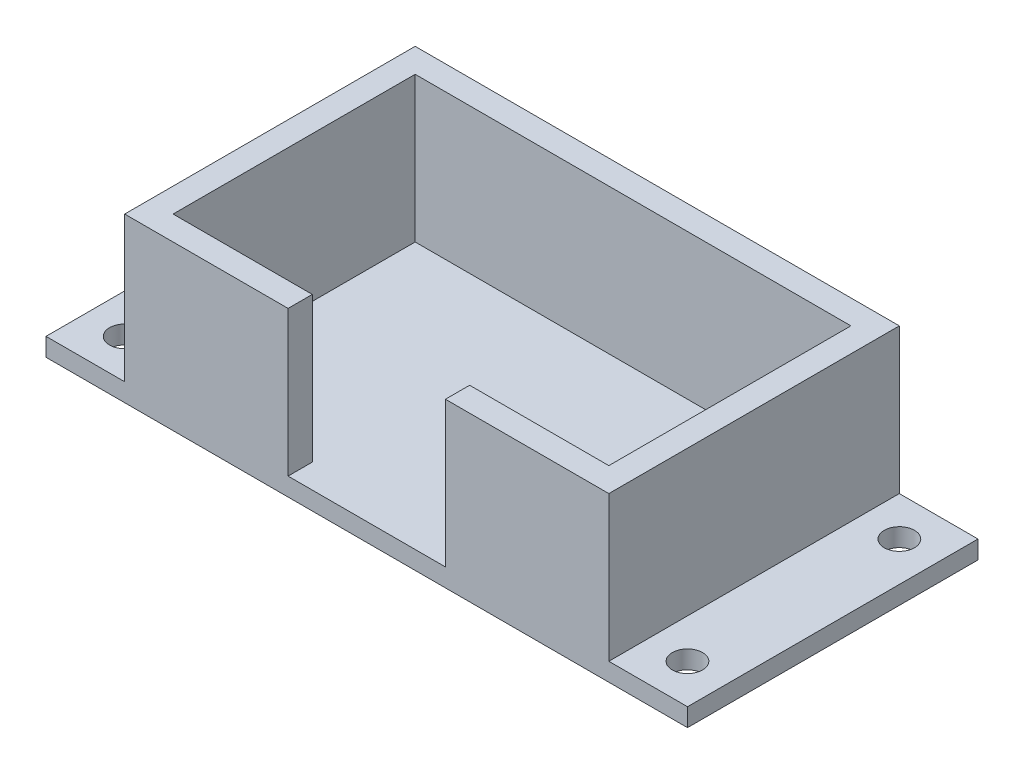
SolidWorks part; units mm, degrees
ref_plane "Front Plane" through (0, 0, 0) normal (0, 0, 1) x (1, 0, 0)
ref_plane "Top Plane" through (0, 0, 0) normal (0, 1, 0) x (1, 0, 0)
ref_plane "Right Plane" through (0, 0, 0) normal (1, 0, 0) x (0, 0, -1)
sketch "Sketch1" plane through (0, 0, 0) normal (0, 1, 0) x (1, 0, 0)
  line L0 (-61.1933, 36.5132) -> (-61.1933, -11.4868)
  line L1 (-61.1933, -11.4868) -> (44.8067, -11.4868)
  line L2 (44.8067, -11.4868) -> (44.8067, 36.5132)
  line L3 (44.8067, 36.5132) -> (-61.1933, 36.5132)
  circle A0 centre (-54.7236, 30.0132) radius 2.5
  circle A1 centre (-54.6902, -4.9868) radius 2.5
  circle A2 centre (38.3156, 30.0132) radius 2.5
  circle A3 centre (38.2979, -4.9868) radius 2.5
  point P4 (0, 0)
  point P7 (-48.6187, 42.6515)
extrude "Boss-Extrude3" add sketch "Sketch1" along normal blind 3
sketch "Sketch3" plane through (0, 3, 0) normal (0, 1, 0) x (1, 0, 0)
  line L0 (-44.1933, 32.5132) -> (-44.1933, -7.4868)
  line L1 (44.8067, 36.5132) -> (-61.1933, 36.5132) construction
  line L2 (-48.1933, 36.5132) -> (31.8067, 36.5132)
  line L3 (31.8067, 36.5132) -> (31.8067, -11.4868)
  line L4 (-61.1933, -11.4868) -> (44.8067, -11.4868) construction
  line L6 (-48.1933, -11.4868) -> (-48.1933, 36.5132)
  line L7 (-44.1933, 32.5132) -> (27.8067, 32.5132)
  line L8 (27.8067, 32.5132) -> (27.8067, -7.4868)
  line L9 (-44.1933, -7.4868) -> (-21.1933, -7.4868)
  line L10 (27.8067, -7.4868) -> (4.8067, -7.4868)
  line L11 (-48.1933, -11.4868) -> (-21.1933, -11.4868)
  line L12 (-21.1933, -11.4868) -> (-21.1933, -7.4868)
  line L13 (4.8067, -7.4868) -> (4.8067, -11.4868)
  line L14 (4.8067, -11.4868) -> (31.8067, -11.4868)
extrude "Boss-Extrude4" add sketch "Sketch3" along normal blind 24
